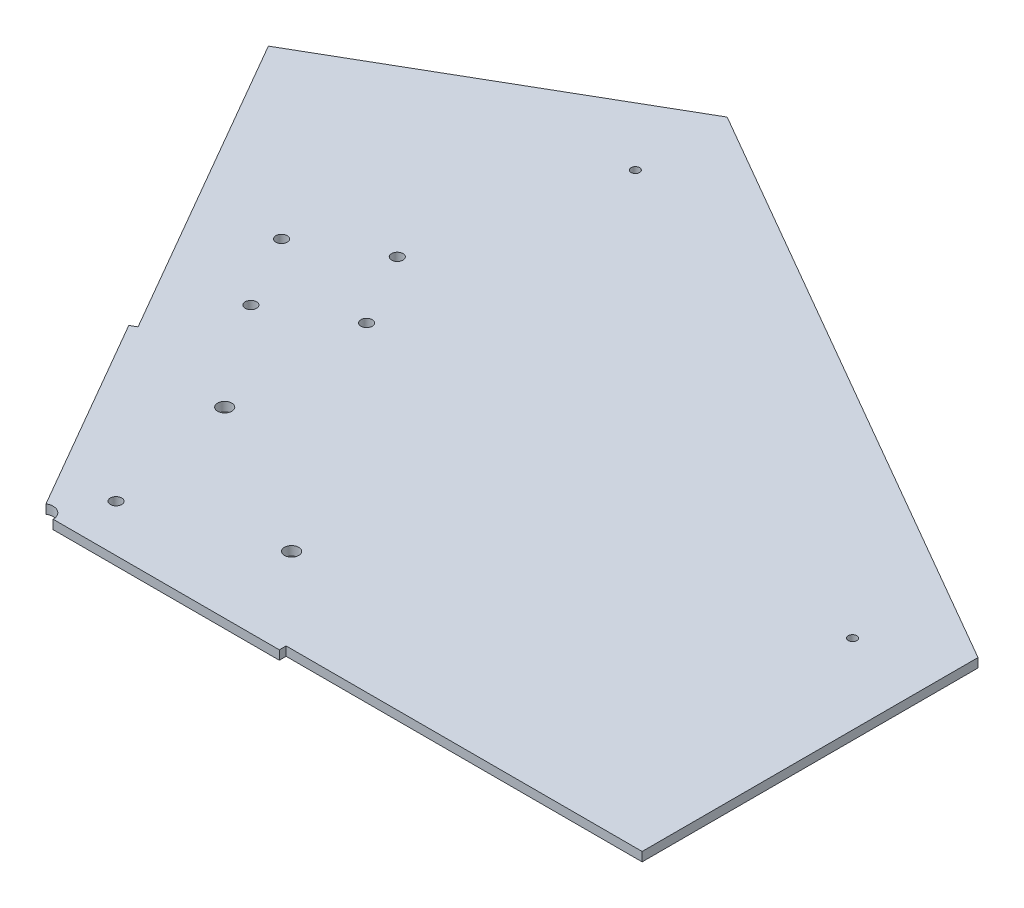
SolidWorks part; units mm, degrees
ref_plane "Front Plane" through (0, 0, 0) normal (0, 0, 1) x (1, 0, 0)
ref_plane "Top Plane" through (0, 0, 0) normal (0, 1, 0) x (1, 0, 0)
ref_plane "Right Plane" through (0, 0, 0) normal (1, 0, 0) x (0, 0, -1)
sketch "Sketch1" plane through (0, 0, 0) normal (0, 1, 0) x (1, 0, 0)
  line L1 (-152.4, -152.4) -> (152.4, -152.4)
  line L2 (-152.4, -152.4) -> (-152.4, 152.4)
  line L3 (-152.4, 152.4) -> (152.4, 152.4)
  line L4 (152.4, -152.4) -> (152.4, 152.4)
  line L5 (-152.4, -152.4) -> (152.4, 152.4) construction
  line L6 (-152.4, 152.4) -> (152.4, -152.4) construction
  line L7 (-208.1823, -120.1941) -> (0, -240.3882)
  line L8 (0, -240.3882) -> (208.1823, -120.1941)
  line L9 (208.1823, -120.1941) -> (208.1823, 120.1941)
  line L10 (208.1823, 120.1941) -> (0, 240.3882)
  line L11 (0, 240.3882) -> (-208.1823, 120.1941)
  line L12 (-208.1823, 120.1941) -> (-208.1823, -120.1941)
  circle A0 centre (0, 0) radius 240.3882 construction
  point P0 (0, 0)
  dimension "D1" = 304.8
  dimension "D2" = 304.8
extrude "Boss-Extrude1" add sketch "Sketch1" along normal blind 3.175 contours L7 L8 L9 L10 L11 L12
sketch "Sketch2" plane through (0, 3.175, 0) normal (0, 1, 0) x (1, 0, 0)
  line L0 (208.1823, -120.1941) -> (208.1823, 120.1941) construction
  line L1 (114.3, 0) -> (-57.15, 98.9867) construction
  line L2 (-57.15, 98.9867) -> (-57.15, -98.9867) construction
  line L3 (-57.15, -98.9867) -> (114.3, 0) construction
  line L5 (83.3, -2.3813) -> (208.1823, -2.3813)
  line L6 (83.3, 2.3813) -> (208.1823, 2.3813)
  line L7 (114.3, -25.4) -> (114.3, 25.4) construction
  line L8 (208.1823, 2.3813) -> (208.1823, -2.3813)
  line L9 (83.3, 2.3813) -> (83.3, -2.3813)
  line L10 (-39.5878, -73.3305) -> (-43.7122, -70.9493)
  line L11 (-43.7122, -70.9493) -> (-106.1534, -179.1005)
  line L12 (-102.0289, -181.4818) -> (-106.1534, -179.1005)
  line L13 (-39.5878, -73.3305) -> (-102.0289, -181.4818)
  line L14 (-43.7122, 70.9493) -> (-39.5878, 73.3305)
  line L15 (-39.5878, 73.3305) -> (-102.0289, 181.4818)
  line L16 (-106.1534, 179.1005) -> (-102.0289, 181.4818)
  line L17 (-43.7122, 70.9493) -> (-106.1534, 179.1005)
  line L18 (-79.147, -86.2867) -> (-35.153, -111.6867) construction
  line L19 (-35.153, 111.6867) -> (-79.147, 86.2867) construction
  line L20 (114.3, 0) -> (114.3, -26.9875) construction
  line L21 (101.6, -26.9875) -> (127, -26.9875) construction
  line L22 (101.6, -26.9875) -> (99.6, -26.9875) construction
  line L23 (99.6, -26.9875) -> (99.6, -56.7055) construction
  line L24 (127, -26.9875) -> (129, -26.9875) construction
  line L25 (129, -26.9875) -> (129, -56.7055) construction
  line L26 (-208.1823, 0) -> (-157.3823, 0)
  line L27 (-208.1823, 120.1941) -> (-208.1823, -120.1941) construction
  line L28 (-157.3823, 50.8) -> (-157.3823, -50.8)
  line L29 (-182.7823, -25.4) -> (-182.7823, 25.4)
  circle A1 centre (0, 0) radius 114.3 construction
  circle A2 centre (99.6, -26.9875) radius 2
  circle A3 centre (99.6, -56.7055) radius 2
  circle A4 centre (129, -26.9875) radius 2
  circle A5 centre (129, -56.7055) radius 2
  circle A6 centre (-73.1719, -72.7624) radius 2
  circle A7 centre (-87.8719, -98.2235) radius 2
  circle A8 centre (-98.9084, -57.9034) radius 2
  circle A9 centre (-113.6084, -83.3645) radius 2
  circle A10 centre (-26.4281, 99.7499) radius 2
  circle A11 centre (-41.1281, 125.211) radius 2
  circle A12 centre (-0.6916, 114.6089) radius 2
  circle A13 centre (-15.3916, 140.07) radius 2
  point P9 (208.1823, 0)
  point P16 (114.3, 0)
  point P18 (83.3, 0)
  point P28 (0, 0)
  point P33 (0, 0)
  point P35 (114.3, -26.9875)
  point P62 (0, 0)
  point P67 (-157.3823, 0)
  point P70 (-182.7823, 0)
  line M7 (-208.1823, -120.1941) -> (0, -240.3882)
  line M11 (0, 240.3882) -> (-208.1823, 120.1941)
  dimension "D1" = 228.6
  dimension "D10" = 4
  dimension "D13" = 4
  dimension "D14" = 3
  dimension "D2" = 4.7625
  dimension "D3" = 50.8
  dimension "D6" = 31
  dimension "D7" = 26.9875
  dimension "D8" = 25.4
  dimension "D9" = 2
  dimension "D11" = 29.718
  dimension "D12" = 2
  dimension "D15" = 50.8
  dimension "D16" = 101.6
  dimension "D17" = 50.8
  dimension "D4" = 3
  dimension "D5" = 3
extrude "Cut-Extrude1" cut sketch "Sketch2" against normal through all contours L17 L14 L15 M11 | A3 | A5 | A4 | A2 | A8 | A7 | A9 | L13 L10 L11 M7 | A6 | A11 | A10 | L6 L8 L5 L9 | A13 | A12
sketch "Sketch3" plane through (0, 3.175, 0) normal (0, 1, 0) x (1, 0, 0)
  circle A0 centre (0, 0) radius 3.9688
  dimension "D1" = 7.9375
extrude "Cut-Extrude3" cut sketch "Sketch3" against normal through all contours A0
sketch "Sketch4" plane through (0, 3.175, 0) normal (0, 1, 0) x (1, 0, 0)
  line L0 (114.3, 0) -> (-57.15, 98.9867) construction
  line L1 (-57.15, 98.9867) -> (-57.15, -98.9867) construction
  line L2 (-57.15, -98.9867) -> (114.3, 0) construction
  line L3 (114.3, -25.4) -> (114.3, 25.4) construction
  line L4 (-79.147, -86.2867) -> (-35.153, -111.6867) construction
  line L5 (-35.153, 111.6867) -> (-79.147, 86.2867) construction
  line L6 (-43.7122, 70.9493) -> (-39.5878, 73.3305) construction
  line L9 (-39.5878, -73.3305) -> (-43.7122, -70.9493) construction
  line L10 (83.3, 2.3813) -> (83.3, -2.3813) construction
  circle A0 centre (0, 0) radius 114.3 construction
  point P7 (114.3, 0)
  point P17 (-57.15, -98.9867)
  dimension "D1" = 228.6
  dimension "D2" = 50.8
sketch "Sketch5" plane through (0, 3.175, 0) normal (0, 1, 0) x (1, 0, 0)
  line L0 (0, 0) -> (9.525, 16.4978)
  circle A0 centre (9.525, 16.4978) radius 2
  circle A1 centre (9.525, -16.4978) radius 2
  circle A2 centre (-19.05, 0) radius 2
  point P11 (0, 0)
  dimension "D3" = 4
  dimension "D1" = 19.05
  dimension "D2" = 60
  dimension "D4" = 3
extrude "Cut-Extrude4" cut sketch "Sketch5" against normal blind 3.175
sketch "Sketch7" plane through (0, 3.175, 0) normal (0, 1, 0) x (1, 0, 0)
  line L0 (0, 0) -> (0, 64.1337)
  line L2 (0, 0) -> (9.525, 16.4978) construction
  circle A0 centre (0, 64.1337) radius 2.5
  circle A1 centre (55.5414, 32.0669) radius 2.5
  circle A2 centre (55.5414, -32.0669) radius 2.5
  circle A3 centre (0, -64.1337) radius 2.5
  circle A4 centre (-55.5414, -32.0669) radius 2.5
  circle A5 centre (-55.5414, 32.0669) radius 2.5
  point P16 (0, 0)
  dimension "D2" = 5
  dimension "D1" = 64.1337
  dimension "D4" = 30
  dimension "D3" = 6
extrude "Cut-Extrude6" cut sketch "Sketch7" against normal through all
sketch "Sketch8" plane through (0, 3.175, 0) normal (0, 1, 0) x (1, 0, 0)
  line L0 (189.4767, 109.3944) -> (185.5944, 94.9055)
  line L1 (208.1823, 2.3813) -> (208.1823, 120.1941) construction
  line L2 (189.4767, 109.3944) -> (174.9878, 113.2767)
  line L3 (208.1823, 120.1941) -> (152.4, 87.9882)
  line L4 (174.9878, 113.2767) -> (171.1055, 98.7878)
  line L5 (171.1055, 98.7878) -> (185.5944, 94.9055)
  line L6 (171.1055, -98.7878) -> (174.9878, -113.2767)
  line L7 (189.4767, -109.3944) -> (174.9878, -113.2767)
  line L8 (174.9878, 113.2767) -> (185.5944, 94.9055)
  line L9 (-152.4, -152.4) -> (152.4, -152.4)
  line L10 (-152.4, -152.4) -> (-152.4, 152.4)
  line L11 (-152.4, 152.4) -> (152.4, 152.4)
  line L12 (152.4, -152.4) -> (152.4, 152.4)
  line L13 (-152.4, -152.4) -> (152.4, 152.4) construction
  line L14 (-152.4, 152.4) -> (152.4, -152.4) construction
  line L15 (189.4767, -109.3944) -> (185.5944, -94.9055)
  line L16 (185.5944, -94.9055) -> (171.1055, -98.7878)
  line L17 (0, -197.5757) -> (-10.6066, -208.1823)
  line L18 (0, -218.7889) -> (-10.6066, -208.1823)
  line L19 (0, -218.7889) -> (10.6066, -208.1823)
  line L20 (10.6066, -208.1823) -> (0, -197.5757)
  line L21 (-171.1055, -98.7878) -> (-185.5944, -94.9055)
  line L22 (-189.4767, -109.3944) -> (-185.5944, -94.9055)
  line L23 (-189.4767, -109.3944) -> (-174.9878, -113.2767)
  line L24 (-174.9878, -113.2767) -> (-171.1055, -98.7878)
  line L25 (-171.1055, 98.7878) -> (-174.9878, 113.2767)
  line L26 (-189.4767, 109.3944) -> (-174.9878, 113.2767)
  line L27 (-189.4767, 109.3944) -> (-185.5944, 94.9055)
  line L28 (-185.5944, 94.9055) -> (-171.1055, 98.7878)
  line L29 (0, 197.5757) -> (10.6066, 208.1823)
  line L30 (0, 218.7889) -> (10.6066, 208.1823)
  line L31 (0, 218.7889) -> (-10.6066, 208.1823)
  line L32 (-10.6066, 208.1823) -> (0, 197.5757)
  circle A0 centre (180.2911, 104.0911) radius 1.5
  circle A1 centre (180.2911, -104.0911) radius 1.5
  circle A2 centre (0, -208.1823) radius 1.5
  circle A3 centre (-180.2911, -104.0911) radius 1.5
  circle A4 centre (-180.2911, 104.0911) radius 1.5
  circle A5 centre (0, 208.1823) radius 1.5
  point P3 (180.2911, 104.0911)
  point P12 (0, 0)
  point P29 (0, 0)
  point P34 (0, 0)
  dimension "D7" = 3
  dimension "D1" = 90
  dimension "D2" = 15
  dimension "D3" = 15
  dimension "D4" = 60
  dimension "D5" = 304.8
  dimension "D6" = 304.8
  dimension "D8" = 6
  dimension "D9" = 6
extrude "Cut-Extrude7" cut sketch "Sketch8" against normal through all contours L3 A0 L8 | L8 A0 L3 | L3 A0 L8 | L8 A0 L3 | A2 | A1 | A5 | A3 | A4
sketch "Sketch6" plane through (0, 3.175, 0) normal (0, 1, 0) x (1, 0, 0)
  line L0 (0, 0) -> (-127, 219.9705)
  line L2 (0, 0) -> (254, 0)
  arc A0 (-127, 219.9705) -> (254, 0) centre (0, 0) ccw
  dimension "D2" = 254
  dimension "D1" = 120
extrude "Cut-Extrude5" cut sketch "Sketch6" against normal blind 3.175
